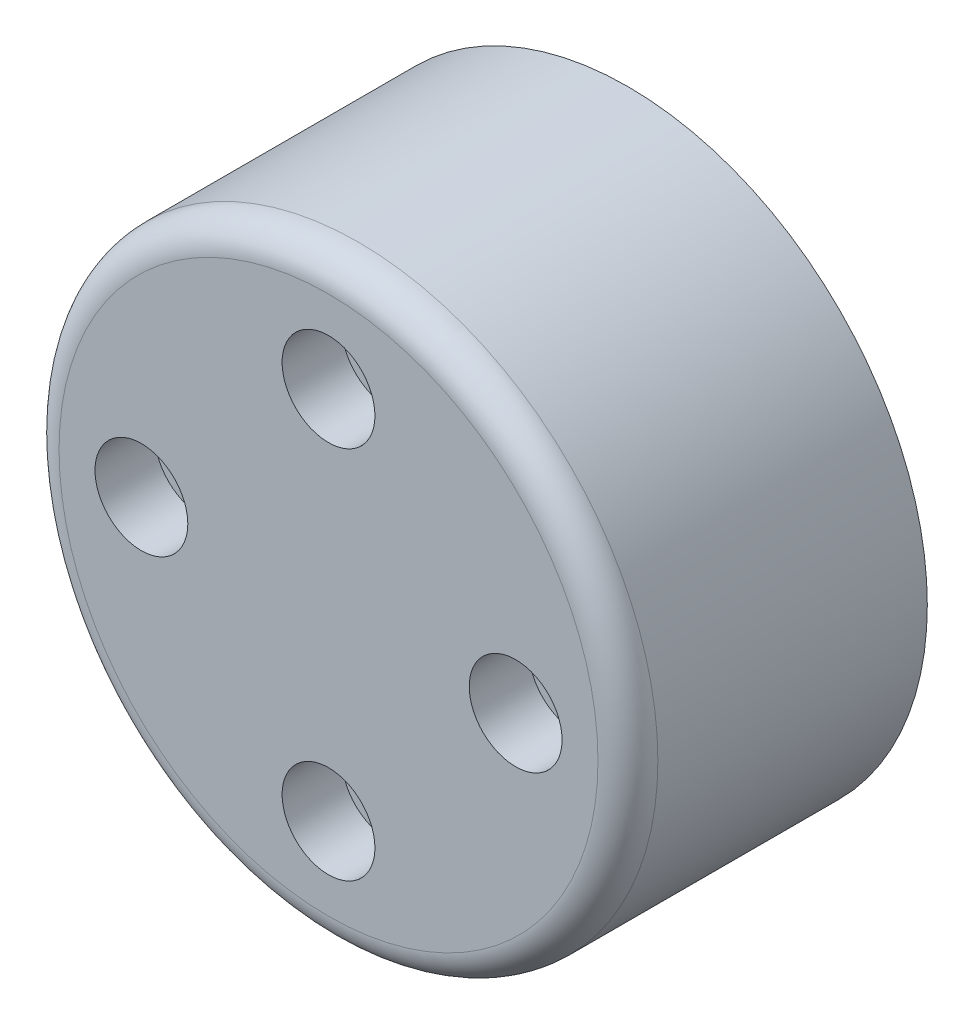
SolidWorks part; units mm, degrees
ref_plane "前视基准面" through (0, 0, 0) normal (0, 0, 1) x (1, 0, 0)
ref_plane "上视基准面" through (0, 0, 0) normal (0, 1, 0) x (1, 0, 0)
ref_plane "右视基准面" through (0, 0, 0) normal (1, 0, 0) x (0, 0, -1)
sketch "草图1" plane through (0, 0, 0) normal (0, 0, 1) x (1, 0, 0)
  line L0 (-12.5, 0) -> (12.5, 0) construction
  line L1 (0, 12.5) -> (0, -12.5) construction
  circle A0 centre (0, 0) radius 20
  circle A1 centre (0, 0) radius 12.5 construction
  circle A2 centre (12.5, 0) radius 1.6
  circle A3 centre (0, -12.5) radius 1.6
  circle A4 centre (-12.5, 0) radius 1.6
  circle A5 centre (0, 12.5) radius 1.6
  dimension "D1" = 25
  dimension "D2" = 40
  dimension "D3" = 3.2
  dimension "D4" = 3.2
extrude "凸台-拉伸1" add sketch "草图1" along normal blind 20
sketch "草图2" plane through (0, 0, 20) normal (0, 0, 1) x (1, 0, 0)
  circle A0 centre (-12.5, 0) radius 3.1
  circle A1 centre (0, -12.5) radius 3.1
  circle A2 centre (12.5, 0) radius 3.1
  circle A3 centre (0, 12.5) radius 3.1
  dimension "D1" = 6.2
  dimension "D2" = 6.2
  dimension "D3" = 6.2
  dimension "D4" = 6.2
extrude "切除-拉伸1" cut sketch "草图2" against normal blind 4
sketch "草图3" plane through (0, 0, 0) normal (0, 0, -1) x (-1, 0, 0)
  line L0 (-12.5, 0) -> (0, 0) construction
  line L1 (0, 0) -> (0, 12.5) construction
  line L2 (0, 0) -> (-6.7175, 6.7175) construction
  circle A0 centre (0, 0) radius 9.5 construction
  circle A1 centre (-6.7175, 6.7175) radius 3.1
  circle A2 centre (6.7175, 6.7175) radius 3.1
  circle A3 centre (6.7175, -6.7175) radius 3.1
  circle A4 centre (-6.7175, -6.7175) radius 3.1
  point P18 (0, 0)
  dimension "D1" = 19
  dimension "D3" = 6.2
  dimension "D5" = 13.435
  dimension "D6" = 6.7175
  dimension "D2" = 45
  dimension "D4" = 4
extrude "切除-拉伸2" cut sketch "草图3" against normal blind 5
fillet "圆角1" radius 2 1 edges at (20, 0, 20)
